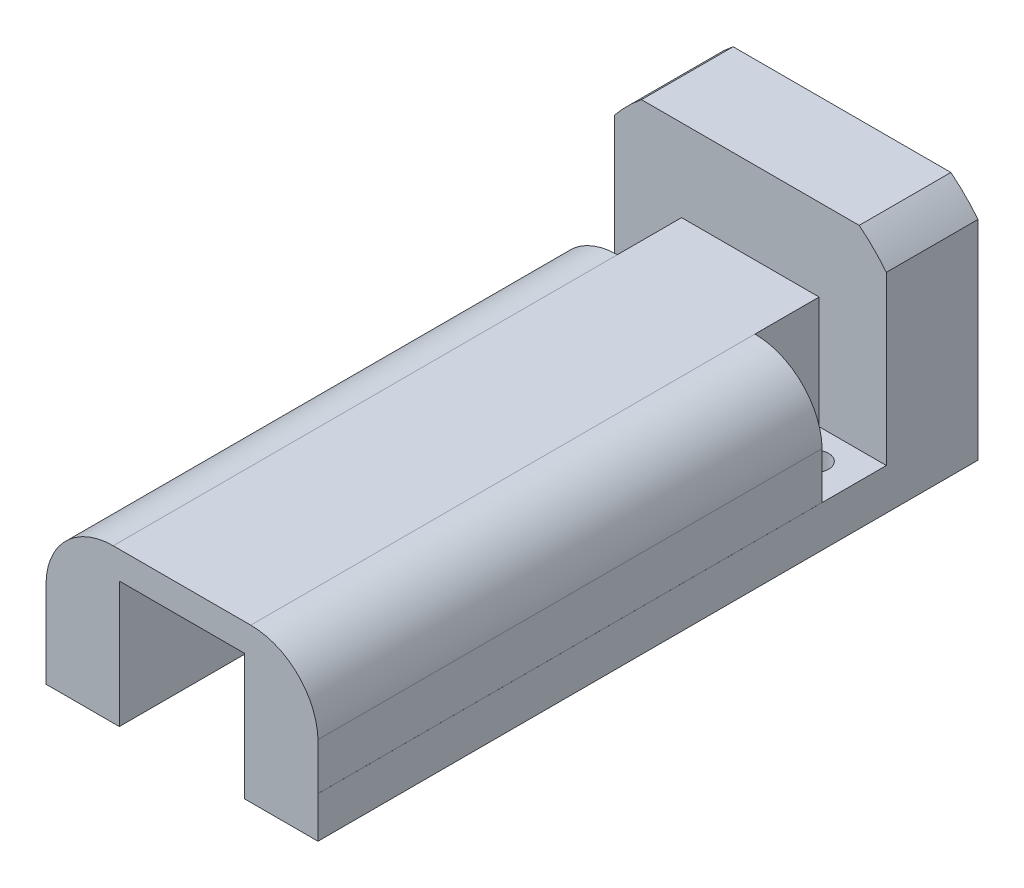
SolidWorks part; units mm, degrees
ref_plane "Front Plane" through (0, 0, 0) normal (0, 0, 1) x (1, 0, 0)
ref_plane "Top Plane" through (0, 0, 0) normal (0, 1, 0) x (1, 0, 0)
ref_plane "Right Plane" through (0, 0, 0) normal (1, 0, 0) x (0, 0, -1)
sketch "Sketch1" plane through (0, 0, 0) normal (0, 0, 1) x (1, 0, 0)
  line L0 (0, 0) -> (0, 29.3495) construction
  line L1 (-14.835, 0) -> (-6.835, 0)
  line L4 (-14.835, 0) -> (-14.835, 4.5)
  line L5 (-14.835, 4.5) -> (-8.35, 4.5)
  line L6 (14.835, 0) -> (14.835, 4.5)
  line L7 (14.835, 0) -> (6.835, 0)
  line L11 (8.35, 4.5) -> (14.835, 4.5)
  line L12 (-8.35, 4.5) -> (8.35, 4.5) construction
  line L13 (-6.835, 0) -> (6.835, 0) construction
  line L14 (-6.835, 0) -> (-6.835, 3)
  line L15 (6.835, 0) -> (6.835, 3)
  line L16 (-6.835, 3) -> (6.835, 3)
  line L17 (-8.35, 4.5) -> (8.35, 4.5)
  point P10 (0, 21.4888)
  point P13 (0, 23.4888)
  point P16 (0, 0)
  dimension "D1" = 29.67
  dimension "D2" = 8
  dimension "D3" = 3
  dimension "D4" = 4.5
extrude "Boss-Extrude1" add sketch "Sketch1" against normal blind 72 contours L15 L16 L14 L1 L4 L5 L17 L11 L6 L7
sketch "Sketch8" plane through (0, 0, -72) normal (0, 0, -1) x (-1, 0, 0)
  line L4 (-14.835, 25.7079) -> (14.835, 25.7079)
  line L8 (0, 0) -> (0, 41.6063) construction
  line L10 (-10.35, 0) -> (-10.35, 21.2229)
  line L11 (14.835, 0) -> (14.835, 25.7079)
  line L12 (10.35, 0) -> (14.835, 0)
  line L13 (-14.835, 0) -> (-10.35, 0)
  line L14 (-10.35, 21.2229) -> (10.35, 21.2229)
  line L15 (10.35, 21.2229) -> (10.35, 0)
  line L16 (-14.835, 0) -> (-6.835, 0) construction
  line L19 (-14.835, 0) -> (-14.835, 25.7079)
  arc A1 (14.8327, 22.748) -> (11.874, 25.7067) centre (0, 10.874) ccw construction
  point P26 (0, 25.7079)
  dimension "D1" = 4.485
  dimension "D2" = 4.485
  dimension "D3" = 25.7079
extrude "Boss-Extrude3" add sketch "Sketch8" against normal blind 5
sketch "Sketch9" plane through (0, 0, -72) normal (0, 0, -1) x (-1, 0, 0)
  line L0 (-15.0091, 25.8819) -> (-15.0091, 22.5275)
  line L7 (-13.437, 24.3098) -> (-15.0091, 25.8819) construction
  line L9 (-15.0091, 25.8819) -> (-11.6546, 25.8819)
  line L10 (-14.835, 25.7079) -> (14.835, 25.7079) construction
  line L11 (0, 0) -> (0, 25.7079) construction
  line L12 (15.0091, 25.8819) -> (15.0091, 22.5275)
  line L13 (15.0091, 25.8819) -> (11.6546, 25.8819)
  arc A1 (-11.6546, 25.8819) -> (-15.0091, 22.5275) centre (-0.0019, 10.8748) ccw
  arc A3 (11.6546, 25.8819) -> (15.0091, 22.5275) centre (0.0019, 10.8748) cw
  dimension "D2" = 19
  dimension "D1" = 45
  dimension "D3" = 3.3544
  dimension "D4" = 0.1741
extrude "Cut-Extrude4" cut sketch "Sketch9" against normal up to surface (5 mm away) up to face at (0, 13.9827, -67)
sketch "Sketch11" plane through (0, 0, -67) normal (0, 0, 1) x (1, 0, 0)
  line L8 (14.835, 4.5) -> (14.835, 22.7483) construction
  line L9 (11.8754, 25.7079) -> (-11.8754, 25.7079) construction
  line L10 (-14.835, 4.5) -> (-14.835, 22.7483) construction
  line L11 (14.835, 4.5) -> (14.835, 22.7483)
  line L12 (11.8754, 25.7079) -> (-11.8754, 25.7079)
  line L13 (-14.835, 4.5) -> (-14.835, 22.7483)
  line L14 (-14.835, 4.5) -> (14.835, 4.5)
  arc A4 (14.835, 22.7483) -> (11.8754, 25.7079) centre (0.0019, 10.8748) ccw construction
  arc A5 (-11.8754, 25.7079) -> (-14.835, 22.7483) centre (-0.0019, 10.8748) ccw construction
  arc A6 (14.835, 22.7483) -> (11.8754, 25.7079) centre (0.0019, 10.8748) ccw
  arc A7 (-11.8754, 25.7079) -> (-14.835, 22.7483) centre (-0.0019, 10.8748) ccw
extrude "Boss-Extrude4" add sketch "Sketch11" along normal blind 5
sketch "Sketch12" plane through (0, 0, -62) normal (0, 0, 1) x (1, 0, 0)
  line L1 (0, 0) -> (0, 30.5664) construction
  line L6 (14.8327, 0) -> (14.8327, 22.748) construction
  line L11 (7.5, 16.75) -> (-7.5, 16.75) construction
  line L12 (-14.835, 4.5) -> (14.835, 4.5)
  line L14 (-14.835, 9.415) -> (-14.835, 0) construction
  line L15 (14.8327, 4.5) -> (14.8327, 9.6002)
  line L16 (7.5, 16.75) -> (-7.5, 16.75)
  line L17 (-14.835, 9.415) -> (-14.835, 4.5)
  arc A0 (14.835, 9.415) -> (7.5, 16.75) centre (7.5, 9.415) ccw construction
  arc A1 (-7.5, 16.75) -> (-14.835, 9.415) centre (-7.5, 9.415) ccw construction
  arc A2 (14.8327, 9.6002) -> (7.5, 16.75) centre (7.5, 9.415) ccw
  arc A3 (-7.5, 16.75) -> (-14.835, 9.415) centre (-7.5, 9.415) ccw
  point P8 (0, 4.5)
  point P13 (0, 11.75)
  point P23 (0, 16.75)
extrude "Boss-Extrude5" add sketch "Sketch12" along normal up to surface (55 mm away) from offset 7 up to face at (0, 1.875, 0)
sketch "Sketch18" plane through (0, 0, -72) normal (0, 0, -1) x (-1, 0, 0)
  line L0 (6.835, 0) -> (6.835, 3) construction
  line L2 (-10.35, 4.5) -> (-10.35, 0)
  line L3 (-10.35, 0) -> (-6.835, 0)
  line L5 (10.35, 4.5) -> (-10.35, 4.5)
  line L6 (10.35, 4.5) -> (10.35, 0)
  line L7 (10.35, 0) -> (6.835, 0)
  line L9 (-6.835, 0) -> (-6.835, 3) construction
  line L10 (6.835, 3) -> (-6.835, 3) construction
  line L11 (6.835, 0) -> (6.835, 3)
  line L12 (-6.835, 0) -> (-6.835, 3)
  line L13 (6.835, 3) -> (-6.835, 3)
extrude "Cut-Extrude8" cut sketch "Sketch18" against normal up to surface (5 mm away) up to face at (0, 12.8614, -67)
sketch "Sketch19" plane through (0, 0, -55) normal (0, 0, -1) x (-1, 0, 0)
  line L0 (14.835, 4.5) -> (-14.8327, 4.5) construction
  line L1 (-7.5, 16.75) -> (7.5, 16.75)
  line L2 (-7.5, 16.75) -> (-7.5, 4.5)
  line L3 (-7.5, 4.5) -> (7.5, 4.5)
  line L4 (7.5, 16.75) -> (7.5, 4.5)
  arc A0 (-7.5, 16.75) -> (-14.8327, 9.6002) centre (-7.5, 9.415) ccw construction
  arc A1 (14.835, 9.415) -> (7.5, 16.75) centre (7.5, 9.415) ccw construction
extrude "Boss-Extrude8" add sketch "Sketch19" along normal up to surface (7 mm away) up to face at (0, 17.6793, -62)
sketch "Sketch20" plane through (0, 4.5, 0) normal (0, 1, 0) x (1, 0, 0)
  line L0 (-14.835, 58.5) -> (-7.5, 58.5) construction
  line L1 (-14.835, 62) -> (-14.835, 55) construction
  line L2 (-7.5, 62) -> (-7.5, 55) construction
  line L3 (-10.5425, 62) -> (-10.5425, 55) construction
  line L6 (0, 62) -> (0, 0) construction
  line L7 (11.8754, 62) -> (-11.8754, 62) construction
  circle A0 centre (-10.5425, 58.5) radius 1.5
  circle A1 centre (10.5425, 58.5) radius 1.5
  dimension "D1" = 3
  dimension "D2" = 4.2925
extrude "Cut-Extrude9" cut sketch "Sketch20" against normal up to next
sketch "Sketch21" plane through (0, 0, -72) normal (0, 0, -1) x (-1, 0, 0)
  line L6 (-11.85, 0) -> (11.85, 0)
  line L9 (11.85, 22.7229) -> (11.85, 0)
  line L10 (-11.85, 22.7229) -> (11.85, 22.7229)
  line L11 (-11.85, 0) -> (-11.85, 22.7229)
  line L12 (11.85, 22.7229) -> (11.85, 0)
  line L13 (-11.85, 22.7229) -> (11.85, 22.7229)
  line L14 (-11.85, 0) -> (-11.85, 22.7229)
  dimension "D1" = 1.5
extrude "Cut-Extrude10" cut sketch "Sketch21" against normal blind 7
sketch "Sketch22" plane through (0, 22.7229, 0) normal (0, -1, 0) x (1, 0, 0)
  line L0 (11.85, -65) -> (11.85, -72) construction
  line L1 (-11.85, -65) -> (11.85, -65)
  line L2 (-11.85, -65) -> (-11.85, -68.5)
  line L3 (-11.85, -68.5) -> (11.85, -68.5)
  line L4 (11.85, -65) -> (11.85, -68.5)
  dimension "D1" = 3.5
extrude "Cut-Extrude11" [suppressed] cut sketch "Sketch22" against normal up to surface (2.985 mm away)
sketch "Sketch23" [suppressed] plane through (-11.85, 0, 0) normal (1, 0, 0) x (0, 0, -1)
  line L0 (65, 0) -> (65, 25.7079) construction
  line L1 (65, 22.7229) -> (68.5, 22.7229)
  line L2 (65, 22.7229) -> (65, 3)
  line L3 (65, 3) -> (68.5, 3)
  line L4 (68.5, 22.7229) -> (68.5, 3)
extrude "Cut-Extrude12" [suppressed] cut sketch "Sketch23" against normal through all both and the other way through all
sketch "Sketch24" plane through (0, 0, 0) normal (0, 0, 1) x (1, 0, 0)
  line L0 (6.835, 0) -> (6.835, 3) construction
  line L1 (-6.835, 3) -> (6.835, 3)
  line L2 (-6.835, 3) -> (-6.835, 13.75)
  line L3 (-6.835, 13.75) -> (6.835, 13.75)
  line L4 (6.835, 3) -> (6.835, 13.75)
  line L5 (-7.5, 16.75) -> (7.5, 16.75) construction
  dimension "D1" = 3
extrude "Cut-Extrude13" cut sketch "Sketch24" against normal up to surface (65 mm away) up to face at (0, 6.4307, -65)
